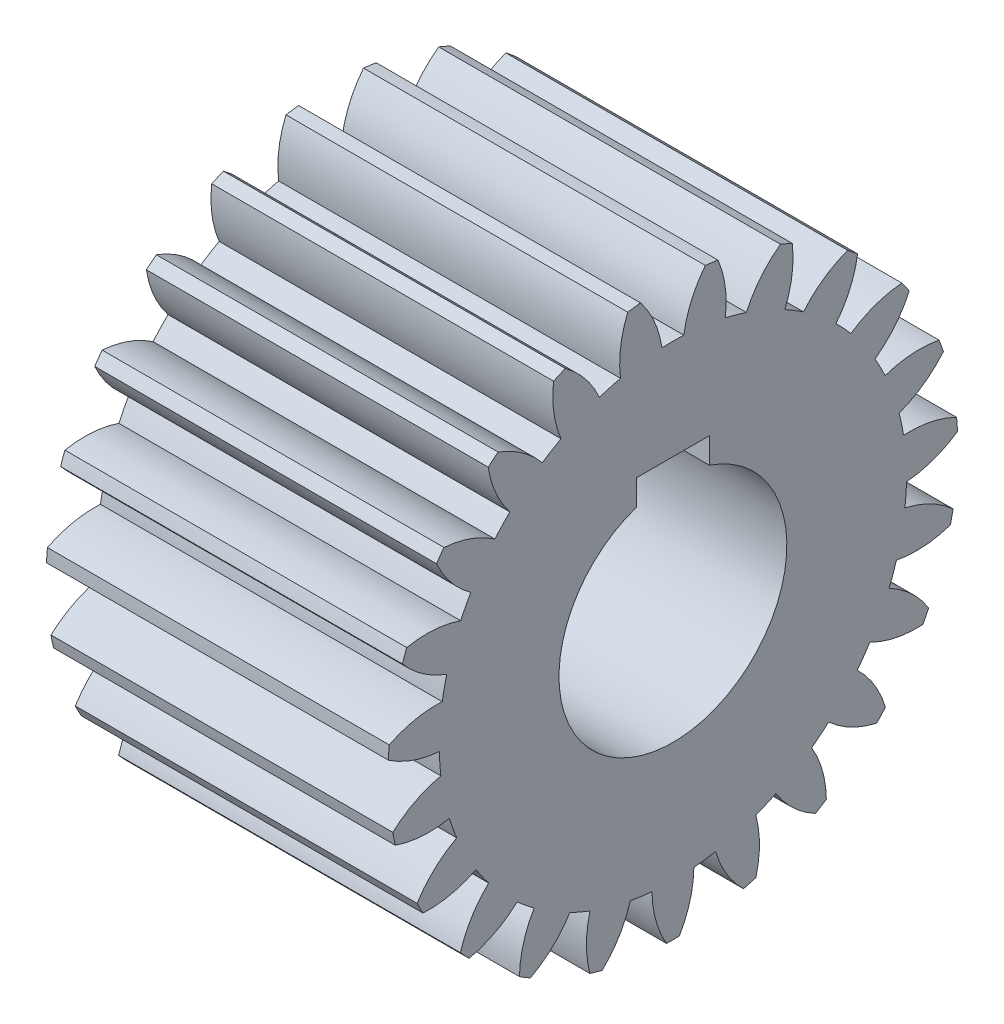
SolidWorks part; units mm, degrees
ref_plane "Plane1" through (0, 0, 0) normal (0, 0, 1) x (1, 0, 0)
ref_plane "Plane2" through (0, 0, 0) normal (0, 1, 0) x (1, 0, 0)
ref_plane "Plane3" through (0, 0, 0) normal (1, 0, 0) x (0, 0, -1)
sketch "HoldingSke" plane through (0, 0, 0) normal (0, 1, 0) x (1, 0, 0)
  line L0 (0, 0) -> (0.1841, -0.0781)
  line L1 (-15, 0) -> (100, 0) construction
  line L2 (0, 0) -> (-2.1039, 2.3779)
  line L3 (0, 0) -> (-11.863, 4.5341)
  line L4 (0, 0) -> (7.9495, 3.3744)
  line L5 (0, 0) -> (-46.8476, -17.4728)
  line L6 (0, 0) -> (-62.1722, -41.9478)
  line L7 (-2.1039, 2.3779) -> (14.0398, 75.6199)
  line L8 (-76.2, 54.61) -> (-71.9, 54.61)
  line L9 (-71.009, 38.7566) -> (-53.1078, 45.2721)
  line L10 (-76.2, 71.12) -> (104.1128, 71.12)
  line L11 (0, 0) -> (-75, 0)
  line L12 (-76.2, 101.6) -> (-76.033, 101.6)
  line L13 (24.9733, 27.94) -> (52.9518, 28.4284)
  line L14 (24.9733, 27.94) -> (24.9743, 27.94)
  line L15 (24.9733, 27.94) -> (100.4006, 29.5858)
  line L16 (-63.627, -5) -> (-12.827, -5)
  circle A0 centre (0, 0) radius 25
  circle A1 centre (0, 0) radius 37.5
  circle A2 centre (0, 0) radius 37.5
  circle A3 centre (0, 0) radius 25
  dimension "MHD" = 75
  dimension "Hub_dia" = 75
  dimension "Bore" = 50
  dimension "MBD" = 50
  dimension "Num_teeth" = 23
  dimension "Pitch" = 0.2
  dimension "Overall_len" = 50
  dimension "Show_teeth" = 23
  dimension "Thickness" = 75
  dimension "OAL" = 75.0001
  dimension "T_dim" = 4.3
  dimension "Ap" = 20
  dimension "H" = 19.05
  dimension "Pitch_radius" = 180.3128
  dimension "Width" = 75
  dimension "Backlash" = 0.167
  dimension "Addendum_fac" = 1
  dimension "Dedendum_fac" = 1.25
  dimension "Clearance_fac" = 0.25
  dimension "Dedendum_add" = 0.001
  dimension "Module" = 5
sketch "BasProSke" plane through (0, 0, 0) normal (0, 1, 0) x (1, 0, 0)
  line L0 (-10, 0) -> (60, 0) construction
  line L1 (0, 0) -> (0, 62.5)
  line L2 (0, 0) -> (75, 0)
  line L3 (75, 0) -> (75, 62.5)
  line L4 (75, 62.5) -> (0, 62.5)
  dimension "Thickness" = 75
  dimension "Diameter" = 125
revolve "Base-Revolve" add sketch "BasProSke" angle 360 about L0
sketch "TooCutSke" plane through (0, 0, 0) normal (1, 0, 0) x (0, 0, -1)
  line L1 (0, 0) -> (0, 107) construction
  line L2 (0, 0) -> (-4.2161, 57.3452) construction
  line L3 (0, 0) -> (-15.6279, 113.7014) construction
  line L4 (-4.2161, 57.3452) -> (-7.8139, 56.8507) construction
  arc A0 (2.4001, 51.1928) -> (-2.4001, 51.1928) centre (0, 0) ccw
  arc A1 (7.134, 62.1171) -> (-7.134, 62.1171) centre (0, 0) ccw
  circle A2 centre (0, 0) radius 57.5 construction
  circle A3 centre (0, 0) radius 54.0323 construction
  arc A4 (-2.4001, 51.1928) -> (-7.134, 62.1171) centre (-25.1516, 47.8214) ccw
  arc A5 (7.134, 62.1171) -> (2.4001, 51.1928) centre (25.1516, 47.8214) ccw
  dimension "Root_dia" = 102.498
  dimension "Overcut_dia" = 125.0508
  dimension "Pitch_dia" = 115
  dimension "Base_dia" = 108.0647
  dimension "Flank_rad" = 23
  dimension "Half_ang" = 7.826
  dimension "Half_CT" = 3.6317
extrude "ToothCut" cut sketch "TooCutSke" along normal through all
fillet "Breaks" [suppressed] radius 0.1
fillet "RootFillets" [suppressed] radius 1.251
pattern_circular "TeethCuts" count 23 every 15.652 about axis through (-10, 0, 0) along (1, 0, 0) of "ToothCut", "RootFillets", "Breaks"
sketch "HubNeaOneSke" plane through (0, 0, 0) normal (-1, 0, 0) x (0, 0, 1)
  circle A0 centre (0, 0) radius 37.5
  dimension "Diameter" = 75
extrude "HubNearOne" [suppressed] add sketch "HubNeaOneSke" along normal blind 12.7001
sketch "HubNeaBotSke" plane through (0, 0, 0) normal (-1, 0, 0) x (0, 0, 1)
  circle A0 centre (0, 0) radius 37.5
  dimension "Diameter" = 75
extrude "HubNearBoth" [suppressed] add sketch "HubNeaBotSke" along normal blind 6.35
ref_plane "FarPln" through (75, 0, 0) normal (1, 0, 0) x (0, 0, -1)
sketch "HubFarSke" plane through (75, 0, 0) normal (1, 0, 0) x (0, 0, -1)
  circle A0 centre (0, 0) radius 37.5
  dimension "Diameter" = 75
extrude "HubFar" [suppressed] add sketch "HubFarSke" along normal blind 6.35
sketch "BorSke" plane through (0, 0, 0) normal (1, 0, 0) x (0, 0, -1)
  circle A0 centre (0, 0) radius 25
  dimension "Diameter" = 50
extrude "Bore" cut sketch "BorSke" along normal mid plane 150.0001
sketch "KeySke" plane through (0, 0, 0) normal (1, 0, 0) x (0, 0, -1)
  line L0 (-8, 0) -> (-8, 29.3)
  line L1 (-8, 29.3) -> (8, 29.3)
  line L2 (8, 29.3) -> (8, 0)
  line L3 (0, 0) -> (0, 34) construction
  line L4 (-8, 0) -> (8, 0)
  dimension "Offset" = 29.3
  dimension "Width" = 16
extrude "Keyway" cut sketch "KeySke" along normal mid plane 150.0001
pattern_circular "Keyway2" [suppressed] count 2 every 90 about axis through (-10, 0, 0) along (1, 0, 0)
equation "' \"Module@HoldingSke\" = 6.35"
equation "' \"Num_teeth@HoldingSke\" = 12"
equation "' \"Ap@HoldingSke\" =  20"
equation "' \"Ap@HoldingSke\" = 20"
equation "' \"Width@HoldingSke\" = 0.5 * 25.4"
equation "' \"Hub_dia@HoldingSke\"= 1 * 25.4"
equation "' \"Hub_dia@HoldingSke\" = 1 * 25.4"
equation "' \"Overall_len@HoldingSke\" = 1.0 * 25.4"
equation "' \"Bore@HoldingSke\" = 0.75 * 25.4"
equation "' \"T_dim@HoldingSke\" = 0.1 * 25.4"
equation "' \"Width@KeySke\" = 0.25 * 25.4"
equation "' \"Show_teeth@HoldingSke\" = 13"
equation "' \"Backlash@HoldingSke\" = 0.009 * 25.4"
equation "' \"Addendum_fac@HoldingSke\" = 1.0"
equation "' \"Dedendum_fac@HoldingSke\" = 1.25"
equation "' \"Dedendum_add@HoldingSke\" = 0.00005 * 25.4"
equation "' \"Clearance_fac@HoldingSke\" = 0.25"
equation "\"Pitch@HoldingSke\" = 1 / \"Module@HoldingSke\""
equation "\"Overcut_dia@TooCutSke\" = (\"Num_teeth@HoldingSke\" + 2 * \"Addendum_fac@HoldingSke\") / \"Pitch@HoldingSke\" + 0.002 * 25.4"
equation "\"Pitch_dia@TooCutSke\" = \"Num_teeth@HoldingSke\" / \"Pitch@HoldingSke\""
equation "\"Base_dia@TooCutSke\" = \"Num_teeth@HoldingSke\" / \"Pitch@HoldingSke\" * cos((\"Ap@HoldingSke\"  * 3.14159265 / 180))"
equation "\"Root_dia@TooCutSke\" = (\"Num_teeth@HoldingSke\" + 2) / \"Pitch@HoldingSke\" - 2 * (\"Addendum_fac@HoldingSke\" + \"Dedendum_fac@HoldingSke\") / \"Pitch@HoldingSke\" - \"Dedendum_add@HoldingSke\" * 2"
equation "\"Half_ang@TooCutSke\" = 180 / \"Num_teeth@HoldingSke\""
equation "\"Half_CT@TooCutSke\" = \"Num_teeth@HoldingSke\" / \"Pitch@HoldingSke\" * sin((3.14159265 / 2 / \"Num_teeth@HoldingSke\")) / 2 - 7 * \"Backlash@HoldingSke\" / 4"
equation "\"Flank_rad@TooCutSke\" = \"Num_teeth@HoldingSke\" / \"Pitch@HoldingSke\" / 5"
equation "\"Radius@RootFillets\" = \"Clearance_fac@HoldingSke\" / \"Pitch@HoldingSke\" + \"Dedendum_add@HoldingSke\""
equation "\"Break_rad@Breaks\" = 0.02 / \"Pitch@HoldingSke\""
equation "\"Thickness@HoldingSke\" = \"Width@HoldingSke\""
equation "\"OAL@HoldingSke\" = \"Thickness@HoldingSke\""
equation "\"MHD@HoldingSke\" = (\"Num_teeth@HoldingSke\" + 2) / \"Pitch@HoldingSke\" - 2 * (\"Addendum_fac@HoldingSke\" + \"Dedendum_fac@HoldingSke\")  / \"Pitch@HoldingSke\" - \"Dedendum_add@HoldingSke\" * 2"
equation "\"MBD@HoldingSke\" = (\"Num_teeth@HoldingSke\" + 2) / \"Pitch@HoldingSke\" - 2 * (\"Addendum_fac@HoldingSke\" + \"Dedendum_fac@HoldingSke\")  / \"Pitch@HoldingSke\" - \"Dedendum_add@HoldingSke\" * 2 - 0.002 * 25.4"
equation "\"MHD@HoldingSke\" = ((sgn( \"MHD@HoldingSke\" - \"Hub_dia@HoldingSke\" )-1)*( \"MHD@HoldingSke\" - \"Hub_dia@HoldingSke\" ))/-2+ \"Hub_dia@HoldingSke\""
equation "\"MBD@HoldingSke\" = ((sgn( \"MBD@HoldingSke\" - \"Bore@HoldingSke\" )-1)*( \"MBD@HoldingSke\" - \"Bore@HoldingSke\" ))/-2+ \"Bore@HoldingSke\""
equation "\"OAL@HoldingSke\" = ((sgn( \"OAL@HoldingSke\" - \"Overall_len@HoldingSke\" )+1)*( \"OAL@HoldingSke\" - \"Overall_len@HoldingSke\" ))/2 + \"Overall_len@HoldingSke\" + 0.000002 * 25.4"
equation "\"Num_teeth@TeethCuts\" = int( \"Show_teeth@HoldingSke\" ) + 1"
equation "\"Num_teeth@TeethCuts\" = ((sgn( \"Num_teeth@TeethCuts\" - \"Num_teeth@HoldingSke\" )-1)*( \"Num_teeth@TeethCuts\" - \"Num_teeth@HoldingSke\" ))/-2+ \"Num_teeth@HoldingSke\""
equation "\"Num_teeth@TeethCuts\" = ((sgn( \"Num_teeth@TeethCuts\" - 2.0)+1)*( \"Num_teeth@TeethCuts\" - 2.0))/2 +2.0"
equation "\"Angle@TeethCuts\" = 360.0 / \"Num_teeth@HoldingSke\""
equation "\"Diameter@BasProSke\" = (\"Num_teeth@HoldingSke\" + 2 * \"Addendum_fac@HoldingSke\") / \"Pitch@HoldingSke\""
equation "\"Thickness@BasProSke\"  = \"Thickness@HoldingSke\""
equation "' \"Fillet_rad@BasProSke\" =  \"Thickness@HoldingSke\" * 0.05"
equation "' \"Fillet_rad@BasProSke\" = \"Thickness@HoldingSke\" * 0.05"
equation "\"MHD@HoldingSke\" = ((sgn( \"MHD@HoldingSke\" - \"Root_dia@TooCutSke\" )-1)*( \"MHD@HoldingSke\" - \"Root_dia@TooCutSke\" ))/-2+ \"Root_dia@TooCutSke\""
equation "\"Diameter@HubNeaOneSke\" = \"MHD@HoldingSke\""
equation "\"Length@HubNearOne\" = \"OAL@HoldingSke\" - \"Thickness@BasProSke\""
equation "\"Diameter@HubNeaBotSke\" = \"MHD@HoldingSke\""
equation "\"Length@HubNearBoth\" = ( \"OAL@HoldingSke\" - \"Thickness@BasProSke\" ) / 2.0"
equation "\"Thickness@FarPln\" = \"Thickness@BasProSke\""
equation "\"Diameter@HubFarSke\" = \"MHD@HoldingSke\""
equation "\"Length@HubFar\" = ( \"OAL@HoldingSke\" - \"Thickness@BasProSke\" ) / 2.0"
equation "\"Diameter@BorSke\" = \"MBD@HoldingSke\""
equation "\"D1@Bore\" = \"OAL@HoldingSke\" * 2.0"
equation "\"D1@Keyway\" = \"OAL@HoldingSke\" * 2.0"
equation "\"Offset@KeySke\" = \"T_dim@HoldingSke\" + \"MBD@HoldingSke\" / 2.0"
